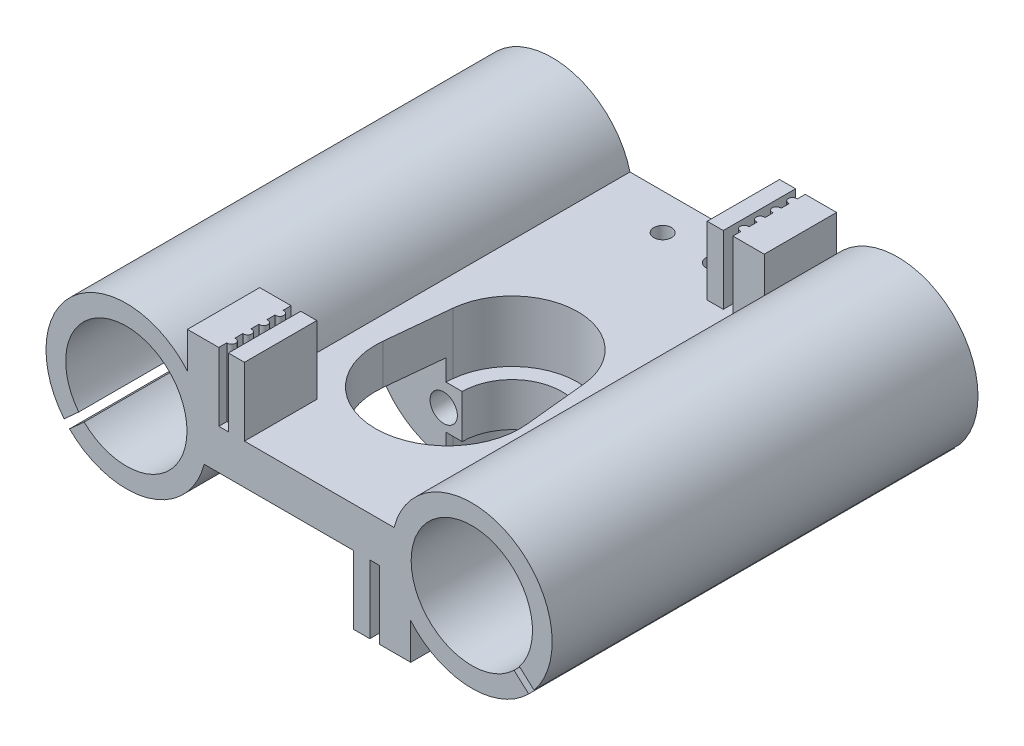
SolidWorks part; units mm, degrees
material "ABS"
ref_plane "Front Plane" through (0, 0, 0) normal (0, 0, 1) x (1, 0, 0)
ref_plane "Top Plane" through (0, 0, 0) normal (0, 1, 0) x (1, 0, 0)
ref_plane "Right Plane" through (0, 0, 0) normal (1, 0, 0) x (0, 0, -1)
sketch "Sketch1" plane through (0, 0, 0) normal (0, 0, 1) x (1, 0, 0)
  line L0 (-11.8175, 2.5) -> (11.8175, 2.5)
  line L1 (-11.8175, -2.5) -> (11.8175, -2.5)
  line L2 (-21.5, 0) -> (21.5, 0) construction
  arc A0 (-11.8175, 2.5) -> (-11.8175, -2.5) centre (-21.5, 0) ccw
  arc A1 (11.8175, -2.5) -> (11.8175, 2.5) centre (21.5, 0) ccw
  dimension "D1" = 20
  dimension "D2" = 43
  dimension "D3" = 5
extrude "Boss-Extrude1" add sketch "Sketch1" along normal mid plane 53
sketch "Sketch2" plane through (0, 0, 26.5) normal (0, 0, 1) x (1, 0, 0)
  circle A0 centre (-21.5, 0) radius 7.55
  circle A1 centre (21.5, 0) radius 7.55
  dimension "D1" = 15.1
extrude "Cut-Extrude1" cut sketch "Sketch2" against normal through all
sketch "Sketch3" plane through (0, 0, 26.5) normal (0, 0, 1) x (1, 0, 0)
  line L0 (-27.1019, -5.0617) -> (-28.9198, -6.7043) construction
  line L1 (-11.8175, -2.5) -> (11.8175, -2.5) construction
  line L2 (-27.4248, -4.6796) -> (-29.2457, -6.3249)
  line L3 (-26.7544, -5.4216) -> (-28.5753, -7.0669)
  line L4 (-21.1648, -0.371) -> (-32.0085, -10.169) construction
  line L5 (-21.5, 0) -> (-32.3437, -9.798) construction
  line L6 (-21.8352, 0.371) -> (-32.6789, -9.427) construction
  line L7 (0, 2.5) -> (0, 16.6971) construction
  line L8 (11.8175, 2.5) -> (-11.8175, 2.5) construction
  line L9 (27.1019, -5.0617) -> (28.9198, -6.7043) construction
  line L10 (26.7544, -5.4216) -> (28.5753, -7.0669)
  line L11 (27.4248, -4.6796) -> (29.2457, -6.3249)
  arc A0 (-11.8175, 2.5) -> (-11.8175, -2.5) centre (-21.5, 0) ccw construction
  arc A1 (-29.2457, -6.3249) -> (-28.5753, -7.0669) centre (-21.5, 0) ccw
  circle A2 centre (-21.5, 0) radius 7.55 construction
  arc A3 (-27.4248, -4.6796) -> (-26.7544, -5.4216) centre (-21.5, 0) ccw
  arc A4 (27.4248, -4.6796) -> (26.7544, -5.4216) centre (21.5, 0) cw
  arc A5 (29.2457, -6.3249) -> (28.5753, -7.0669) centre (21.5, 0) cw
  dimension "D1" = 137.9
  dimension "D2" = 0.5
  dimension "D3" = 0.5
extrude "Cut-Extrude2" cut sketch "Sketch3" against normal through all
sketch "Sketch4" plane through (0, 2.5, 0) normal (0, 1, 0) x (1, 0, 0)
  line L0 (-3.25, 22) -> (3.25, 22) construction
  line L1 (0, 22) -> (0, 26.5) construction
  line L2 (11.8175, 26.5) -> (-11.8175, 26.5) construction
  line L3 (11.8175, -26.5) -> (-11.8175, -26.5) construction
  line L4 (0, -8) -> (0, -26.5) construction
  line L5 (-8.1589, 0.82) -> (-8.9549, -7.1)
  line L7 (8.1589, 0.82) -> (8.9549, -7.1)
  circle A0 centre (-3.25, 22) radius 1.1
  circle A1 centre (3.25, 22) radius 1.1
  arc A2 (8.1589, 0.82) -> (-8.1589, 0.82) centre (0, 0) ccw
  arc A3 (-8.9549, -7.1) -> (8.9549, -7.1) centre (0, -8) ccw
  dimension "D1" = 2.2
  dimension "D2" = 6.5
  dimension "D3" = 4.5
  dimension "D4" = 18
  dimension "D5" = 16.4
  dimension "D6" = 8
  dimension "D7" = 18.5
extrude "Cut-Extrude3" cut sketch "Sketch4" against normal through all
sketch "Sketch5" plane through (0, 2.5, 0) normal (0, 1, 0) x (1, 0, 0)
  line L0 (-8.7967, -26.5) -> (-8.7967, -17.5)
  line L1 (11.8175, -26.5) -> (-11.8175, -26.5) construction
  line L2 (-8.7967, -17.5) -> (-6.7967, -17.5)
  line L3 (-6.7967, -17.5) -> (-6.7967, -26.5)
  line L4 (-6.7967, -26.5) -> (-8.7967, -26.5)
  line L5 (-13.8967, -26.5) -> (-13.8967, -17.5)
  line L6 (-31.5, -26.5) -> (-11.8175, -26.5) construction
  line L7 (-13.8967, -17.5) -> (-9.9967, -17.5)
  line L8 (-9.9967, -17.5) -> (-9.9967, -26.5)
  line L9 (-9.9967, -26.5) -> (-13.8967, -26.5)
  line L10 (-11.8175, -26.5) -> (-11.8175, 26.5) construction
  line L11 (11.8175, 26.5) -> (-11.8175, 26.5) construction
  line L12 (6.7967, 26.5) -> (8.7967, 26.5)
  line L13 (6.7967, 26.5) -> (6.7967, 17.5)
  line L14 (6.7967, 17.5) -> (8.7967, 17.5)
  line L15 (8.7967, 26.5) -> (8.7967, 17.5)
  line L16 (11.8175, -26.5) -> (11.8175, 26.5) construction
  line L17 (9.9967, 26.5) -> (13.8967, 26.5)
  line L18 (9.9967, 26.5) -> (9.9967, 17.5)
  line L19 (9.9967, 17.5) -> (13.8967, 17.5)
  line L20 (13.8967, 26.5) -> (13.8967, 17.5)
  dimension "D1" = 9
  dimension "D2" = 2
  dimension "D3" = 1.2
  dimension "D4" = 3.9
  dimension "D5" = 5.0209
  dimension "D6" = 1.2
  dimension "D7" = 5.0209
extrude "Boss-Extrude2" add sketch "Sketch5" along normal blind 8.5
sketch "Sketch6" plane through (0, 11, 0) normal (0, 1, 0) x (1, 0, 0)
  line L0 (-9.8967, -24.5) -> (-9.9967, -24.5)
  line L1 (-9.8967, -25.5) -> (-9.9967, -25.5)
  line L2 (-9.9967, -26.5) -> (-9.9967, -17.5) construction
  line L3 (-13.8967, -26.5) -> (-9.9967, -26.5) construction
  line L4 (-9.9967, -25.5) -> (-9.9967, -24.5)
  line L5 (-9.8967, -22.5) -> (-9.9967, -22.5)
  line L6 (-9.8967, -23.5) -> (-9.9967, -23.5)
  line L7 (-9.9967, -23.5) -> (-9.9967, -22.5)
  line L8 (-9.8967, -20.5) -> (-9.9967, -20.5)
  line L9 (-9.8967, -21.5) -> (-9.9967, -21.5)
  line L10 (-9.9967, -21.5) -> (-9.9967, -20.5)
  line L11 (-9.8967, -18.5) -> (-9.9967, -18.5)
  line L12 (-9.8967, -19.5) -> (-9.9967, -19.5)
  line L13 (-9.9967, -19.5) -> (-9.9967, -18.5)
  line L14 (9.9967, 26.5) -> (9.9967, 17.5) construction
  line L15 (13.8967, 26.5) -> (9.9967, 26.5) construction
  line L16 (9.9967, 25.5) -> (9.9967, 24.5)
  line L17 (9.8967, 25.5) -> (9.9967, 25.5)
  line L18 (9.8967, 24.5) -> (9.9967, 24.5)
  line L19 (9.9967, 23.5) -> (9.9967, 22.5)
  line L20 (9.8967, 23.5) -> (9.9967, 23.5)
  line L21 (9.8967, 22.5) -> (9.9967, 22.5)
  line L22 (9.9967, 21.5) -> (9.9967, 20.5)
  line L23 (9.8967, 21.5) -> (9.9967, 21.5)
  line L24 (9.8967, 20.5) -> (9.9967, 20.5)
  line L25 (9.9967, 19.5) -> (9.9967, 18.5)
  line L26 (9.8967, 19.5) -> (9.9967, 19.5)
  line L27 (9.8967, 18.5) -> (9.9967, 18.5)
  arc A0 (-9.8967, -25.5) -> (-9.8967, -24.5) centre (-9.8967, -25) ccw
  arc A1 (-9.8967, -23.5) -> (-9.8967, -22.5) centre (-9.8967, -23) ccw
  arc A2 (-9.8967, -21.5) -> (-9.8967, -20.5) centre (-9.8967, -21) ccw
  arc A3 (-9.8967, -19.5) -> (-9.8967, -18.5) centre (-9.8967, -19) ccw
  arc A4 (9.8967, 25.5) -> (9.8967, 24.5) centre (9.8967, 25) ccw
  arc A5 (9.8967, 23.5) -> (9.8967, 22.5) centre (9.8967, 23) ccw
  arc A6 (9.8967, 21.5) -> (9.8967, 20.5) centre (9.8967, 21) ccw
  arc A7 (9.8967, 19.5) -> (9.8967, 18.5) centre (9.8967, 19) ccw
  dimension "D1" = 1
  dimension "D2" = 0.1
  dimension "D3" = 1.5
  dimension "D5" = 0.1
  dimension "D6" = 1.5
  dimension "D7" = 1
  dimension "D4" = 4
  dimension "D8" = 4
extrude "Boss-Extrude3" add sketch "Sketch6" against normal up to next
sketch "Sketch7" plane through (0, 0, 26.5) normal (0, 0, 1) x (1, 0, 0)
  line L0 (-7.5, -13.5) -> (7.5, -13.5)
  line L1 (-11.8175, -2.5) -> (11.8175, -2.5) construction
  line L2 (-11.8175, -2.5) -> (11.8175, -2.5)
  line L3 (0, -2.5) -> (0, -13.5) construction
  arc A0 (7.5, -13.5) -> (16.1792, -8.467) centre (7.5, -3.5) ccw
  arc A1 (-7.5, -13.5) -> (-16.1792, -8.467) centre (-7.5, -3.5) cw
  arc A2 (-28.5753, -7.0669) -> (-11.8175, -2.5) centre (-21.5, 0) ccw construction
  arc A3 (11.8175, -2.5) -> (28.5753, -7.0669) centre (21.5, 0) ccw construction
  arc A4 (-16.1792, -8.467) -> (-11.8175, -2.5) centre (-21.5, 0) ccw
  arc A5 (11.8175, -2.5) -> (16.1792, -8.467) centre (21.5, 0) ccw
  dimension "D2" = 10
  dimension "D1" = 11
  dimension "D3" = 15
extrude "Boss-Extrude4" add sketch "Sketch7" against normal blind 9.5 from offset 26.5 offset against normal yes
sketch "Sketch8" plane through (0, 2.5, 0) normal (0, 1, 0) x (1, 0, 0)
  line L0 (-8.1589, 0.82) -> (-8.9549, -7.1) construction
  line L1 (8.9549, -7.1) -> (8.1589, 0.82) construction
  line L2 (-8.1589, 0.82) -> (-8.2413, 0)
  line L3 (8.2413, 0) -> (8.1589, 0.82)
  line L4 (-8.2413, 0) -> (8.2413, 0)
  arc A0 (8.1589, 0.82) -> (-8.1589, 0.82) centre (0, 0) ccw construction
  arc A1 (8.1589, 0.82) -> (-8.1589, 0.82) centre (0, 0) ccw
extrude "Cut-Extrude4" cut sketch "Sketch8" against normal through all
sketch "Sketch9" plane through (0, 2.5, 0) normal (0, 1, 0) x (1, 0, 0)
  line L0 (8.9549, -7.1) -> (8.1589, 0.82) construction
  line L1 (-6.2, 0) -> (-8.2413, 0)
  line L2 (6.2, 0) -> (8.2413, 0)
  line L3 (-8.1589, 0.82) -> (-8.9549, -7.1) construction
  line L4 (8.2413, 0) -> (8.1589, 0.82)
  line L5 (-8.1589, 0.82) -> (-8.2413, 0)
  arc A0 (6.2, 0) -> (-6.2, 0) centre (0, 0) ccw
  arc A1 (8.1589, 0.82) -> (-8.1589, 0.82) centre (0, 0) ccw construction
  arc A2 (8.1589, 0.82) -> (-8.1589, 0.82) centre (0, 0) ccw
  dimension "D1" = 12.4
extrude "Boss-Extrude5" add sketch "Sketch9" against normal blind 5.4 from offset 7.6 offset against normal yes
sketch "Sketch10" plane through (0, 0, -9.5) normal (0, 0, -1) x (-1, 0, 0)
  line L0 (7.5, -13.5) -> (-7.5, -13.5) construction
  line L1 (-8.5, -8) -> (8.5, -8) construction
  line L2 (0, -13.5) -> (0, -8) construction
  circle A0 centre (-8.5, -8) radius 1.7
  circle A1 centre (8.5, -8) radius 1.7
  dimension "D1" = 3.4
  dimension "D2" = 17
  dimension "D3" = 5.5
extrude "Cut-Extrude5" cut sketch "Sketch10" against normal through all
sketch "Sketch11" plane through (0, 0, -9.5) normal (0, 0, -1) x (-1, 0, 0)
  line L1 (6.8873, -10.7933) -> (10.1127, -10.7933)
  line L2 (10.1127, -10.7933) -> (11.7254, -8)
  line L3 (11.7254, -8) -> (10.1127, -5.2067)
  line L4 (10.1127, -5.2067) -> (6.8873, -5.2067)
  line L5 (6.8873, -5.2067) -> (5.2746, -8)
  line L6 (5.2746, -8) -> (6.8873, -10.7933)
  circle A0 centre (-8.5, -8) radius 3
  circle A1 centre (8.5, -8) radius 2.7933 construction
  dimension "D1" = 6
  dimension "D2" = 3.2254
extrude "Cut-Extrude6" cut sketch "Sketch11" against normal blind 3
sketch "Sketch12" plane through (0, -2.5, 0) normal (0, -1, 0) x (1, 0, 0)
  line L0 (-11.8175, -26.5) -> (11.8175, -26.5) construction
  line L1 (-8.7967, -26.5) -> (-6.7967, -26.5)
  line L2 (-8.7967, -26.5) -> (-8.7967, -17.5)
  line L3 (-8.7967, -17.5) -> (-6.7967, -17.5)
  line L4 (-6.7967, -26.5) -> (-6.7967, -17.5)
  line L5 (-28.5753, -26.5) -> (-11.8175, -26.5) construction
  line L6 (-13.8967, -26.5) -> (-9.9967, -26.5)
  line L7 (-13.8967, -26.5) -> (-13.8967, -17.5)
  line L8 (-13.8967, -17.5) -> (-9.9967, -17.5)
  line L9 (-9.9967, -26.5) -> (-9.9967, -17.5)
  line L10 (-11.8175, 26.5) -> (11.8175, 26.5) construction
  line L11 (6.7967, 26.5) -> (8.7967, 26.5)
  line L12 (6.7967, 26.5) -> (6.7967, 17.5)
  line L13 (6.7967, 17.5) -> (8.7967, 17.5)
  line L14 (8.7967, 26.5) -> (8.7967, 17.5)
  line L15 (-11.8175, -9.5) -> (-11.8175, -26.5) construction
  line L16 (9.9967, 26.5) -> (13.8967, 26.5)
  line L17 (9.9967, 26.5) -> (9.9967, 17.5)
  line L18 (9.9967, 17.5) -> (13.8967, 17.5)
  line L19 (13.8967, 26.5) -> (13.8967, 17.5)
  line L20 (11.8175, 26.5) -> (11.8175, 0) construction
  dimension "D1" = 2
  dimension "D2" = 1.2
  dimension "D3" = 5.0209
  dimension "D4" = 5.0209
  dimension "D5" = 3.9
  dimension "D6" = 9
  dimension "D7" = 1.2
extrude "Boss-Extrude6" add sketch "Sketch12" along normal blind 8.5
sketch "Sketch13" plane through (0, -11, 0) normal (0, -1, 0) x (1, 0, 0)
  line L0 (-9.9967, -26.5) -> (-9.9967, -17.5) construction
  line L1 (-9.9967, -26.5) -> (-8.7967, -26.5) construction
  line L2 (-9.8967, -24.5) -> (-9.9967, -24.5)
  line L3 (-9.8967, -25.5) -> (-9.9967, -25.5)
  line L4 (-9.9967, -25.5) -> (-9.9967, -24.5)
  line L6 (-9.8967, -22.5) -> (-9.9967, -22.5)
  line L7 (-9.8967, -23.5) -> (-9.9967, -23.5)
  line L8 (-9.9967, -23.5) -> (-9.9967, -22.5)
  line L9 (-9.8967, -20.5) -> (-9.9967, -20.5)
  line L10 (-9.8967, -21.5) -> (-9.9967, -21.5)
  line L11 (-9.9967, -21.5) -> (-9.9967, -20.5)
  line L12 (-9.8967, -18.5) -> (-9.9967, -18.5)
  line L13 (-9.8967, -19.5) -> (-9.9967, -19.5)
  line L14 (-9.9967, -19.5) -> (-9.9967, -18.5)
  line L15 (8.7967, 26.5) -> (9.9967, 26.5) construction
  line L16 (9.9967, 26.5) -> (9.9967, 17.5) construction
  line L17 (9.8967, 25.5) -> (9.9967, 25.5)
  line L18 (9.8967, 24.5) -> (9.9967, 24.5)
  line L19 (9.9967, 25.5) -> (9.9967, 24.5)
  line L20 (9.8967, 23.5) -> (9.9967, 23.5)
  line L21 (9.8967, 22.5) -> (9.9967, 22.5)
  line L22 (9.9967, 23.5) -> (9.9967, 22.5)
  line L23 (9.8967, 21.5) -> (9.9967, 21.5)
  line L24 (9.8967, 20.5) -> (9.9967, 20.5)
  line L25 (9.9967, 21.5) -> (9.9967, 20.5)
  line L26 (9.8967, 19.5) -> (9.9967, 19.5)
  line L27 (9.8967, 18.5) -> (9.9967, 18.5)
  line L28 (9.9967, 19.5) -> (9.9967, 18.5)
  arc A0 (-9.8967, -25.5) -> (-9.8967, -24.5) centre (-9.8967, -25) ccw
  arc A1 (-9.8967, -23.5) -> (-9.8967, -22.5) centre (-9.8967, -23) ccw
  arc A2 (-9.8967, -21.5) -> (-9.8967, -20.5) centre (-9.8967, -21) ccw
  arc A3 (-9.8967, -19.5) -> (-9.8967, -18.5) centre (-9.8967, -19) ccw
  arc A4 (9.8967, 25.5) -> (9.8967, 24.5) centre (9.8967, 25) ccw
  arc A5 (9.8967, 23.5) -> (9.8967, 22.5) centre (9.8967, 23) ccw
  arc A6 (9.8967, 21.5) -> (9.8967, 20.5) centre (9.8967, 21) ccw
  arc A7 (9.8967, 19.5) -> (9.8967, 18.5) centre (9.8967, 19) ccw
  dimension "D1" = 1
  dimension "D2" = 0.1
  dimension "D3" = 1.5
  dimension "D5" = 1
  dimension "D6" = 1.5
  dimension "D7" = 0.1
  dimension "D4" = 4
  dimension "D8" = 4
extrude "Boss-Extrude7" add sketch "Sketch13" against normal up to next
